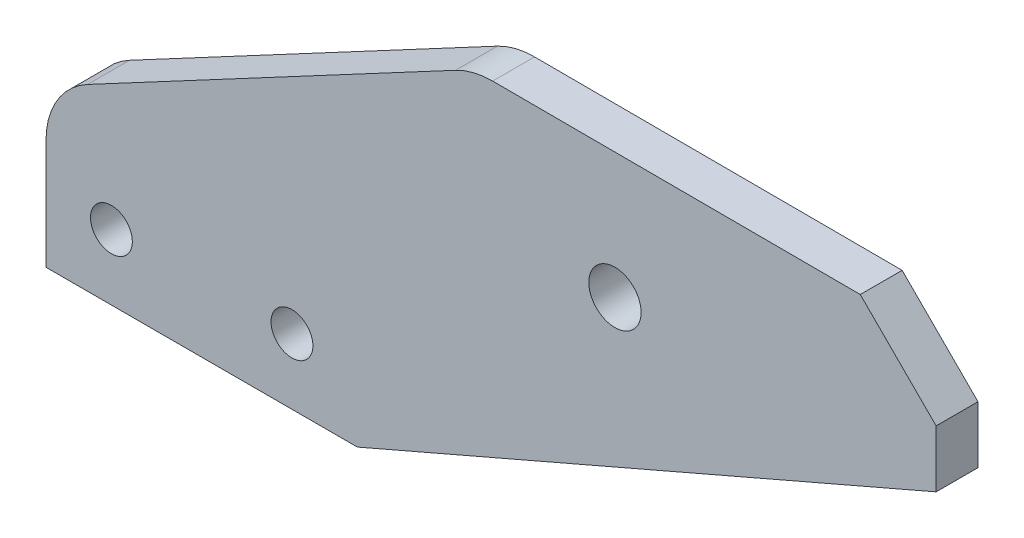
SolidWorks part; units mm, degrees
ref_plane "Front Plane" through (0, 0, 0) normal (0, 0, 1) x (1, 0, 0)
ref_plane "Top Plane" through (0, 0, 0) normal (0, 1, 0) x (1, 0, 0)
ref_plane "Right Plane" through (0, 0, 0) normal (1, 0, 0) x (0, 0, -1)
sketch "Sketch1" plane through (0, 0, 0) normal (0, 0, 1) x (1, 0, 0)
  line L0 (0, 0) -> (0, 10.6678)
  line L1 (0, -55) -> (0, 55) construction
  line L2 (0, 0) -> (30.226, 0)
  line L3 (55, 0) -> (-55, 0) construction
  line L5 (86.4102, 29.8737) -> (79.0464, 37.2375)
  line L6 (79.0464, 37.2375) -> (43.363, 37.3378)
  line L7 (39.756, 36.4415) -> (4.0343, 17.3915)
  line L8 (30.226, 0) -> (30.226, 31.3308) construction
  line L9 (79.0464, 37.2375) -> (79.0464, 25.9956) construction
  line L10 (30.226, 0) -> (86.4102, 24.3253)
  line L11 (86.4102, 24.3253) -> (86.4102, 29.8737)
  line L12 (23.876, 6.35) -> (51.4698, 6.35) construction
  line L13 (44.8926, 6.35) -> (44.8926, 0) construction
  line L14 (86.4102, 24.3253) -> (86.4102, 0) construction
  line L15 (86.4102, 15.24) -> (17.5762, 15.24) construction
  line L16 (17.5762, 15.24) -> (17.5762, 38.5298) construction
  line L17 (55.7206, 16.297) -> (55.7206, -2.0034) construction
  line L18 (86.4102, 24.3253) -> (86.3515, -6.6807) construction
  line L19 (86.3599, -0.1109) -> (86.315, -35.0394) construction
  line L20 (86.3515, -6.6807) -> (55.7206, -2.0034) construction
  arc A0 (39.756, 36.4415) -> (43.363, 37.3378) centre (43.3416, 29.7179) cw
  arc A1 (0, 10.6678) -> (4.0343, 17.3915) centre (7.62, 10.6678) cw
  circle A2 centre (6.35, 6.35) radius 2.032
  circle A3 centre (23.876, 6.35) radius 2.032
  circle A6 centre (55.2307, 25.0858) radius 2.54
  point P21 (41.4468, 37.3432)
  point P24 (0, 15.24)
  dimension "D9" = 7.62
  dimension "D11" = 4.064
  dimension "D12" = 6.35
  dimension "D13" = 6.35
  dimension "D14" = 4.064
  dimension "D15" = 6.35
  dimension "D16" = 6.35
  dimension "D19" = 5.08
  dimension "D1" = 15.24
  dimension "D2" = 30.226
  dimension "D3" = 61.2241
  dimension "D4" = 10.414
  dimension "D5" = 5.5484
  dimension "D6" = 135.161
  dimension "D7" = 37.5996
  dimension "D8" = 46.9722
  dimension "D10" = 86.4102
  dimension "D17" = 21.0166
  dimension "D18" = 68.834
  dimension "D21" = 30.9859
extrude "Boss-Extrude1" add sketch "Sketch1" against normal blind 4.064
